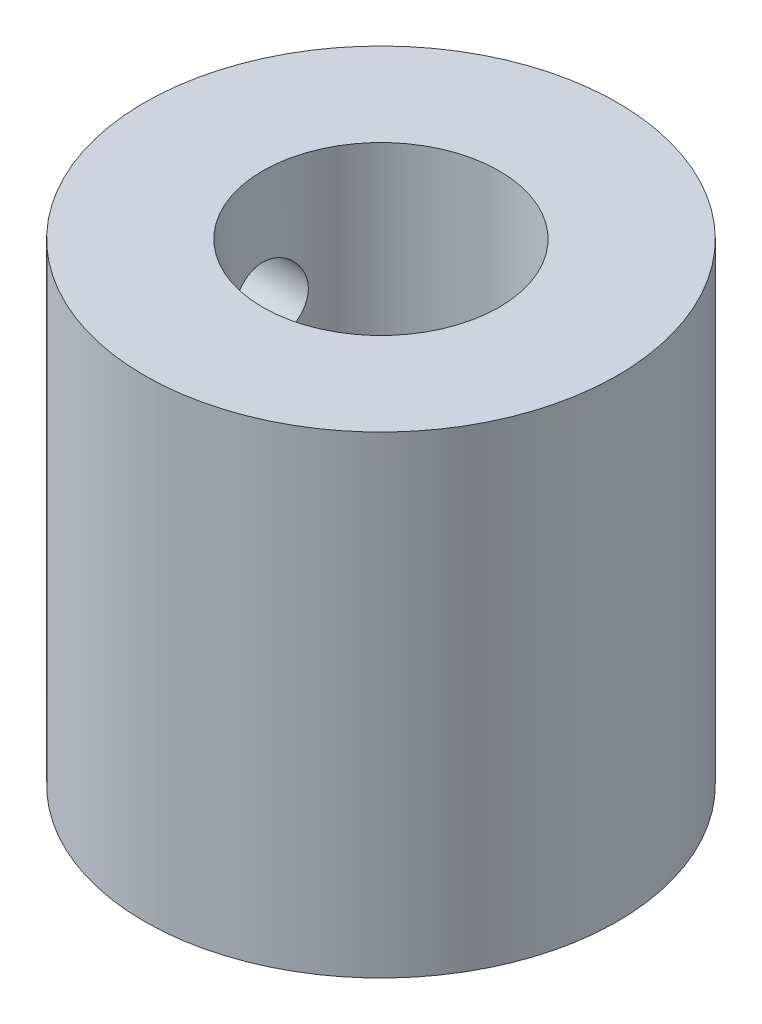
SolidWorks part; units mm, degrees
material "6061 Alloy"
ref_plane "Front Plane" through (0, 0, 0) normal (0, 0, 1) x (1, 0, 0)
ref_plane "Top Plane" through (0, 0, 0) normal (0, 1, 0) x (1, 0, 0)
ref_plane "Right Plane" through (0, 0, 0) normal (1, 0, 0) x (0, 0, -1)
sketch "Sketch1" plane through (0, 0, 0) normal (0, 1, 0) x (1, 0, 0)
  circle A0 centre (0, 0) radius 10
  circle A1 centre (0, 0) radius 4
  dimension "D1" = 20
  dimension "D2" = 8
extrude "Boss-Extrude1" add sketch "Sketch1" along normal blind 20
sketch "Sketch2" plane through (0, 20, 0) normal (0, 1, 0) x (1, 0, 0)
  circle A0 centre (0, 0) radius 5
  dimension "D1" = 10
extrude "Cut-Extrude1" cut sketch "Sketch2" against normal blind 10
sketch "Sketch3" plane through (0, 0, 0) normal (1, 0, 0) x (0, 0, -1)
  line L0 (0, 20) -> (0, 0) construction
  line L1 (5, 20) -> (-5, 20) construction
  line L2 (-10, 0) -> (10, 0) construction
  circle A0 centre (0, 5) radius 1.65
  circle A1 centre (0, 15) radius 1.65
  dimension "D1" = 3.3
  dimension "D2" = 3.3
  dimension "D4" = 5
  dimension "D3" = 10
extrude "Cut-Extrude2" cut sketch "Sketch3" against normal blind 10
